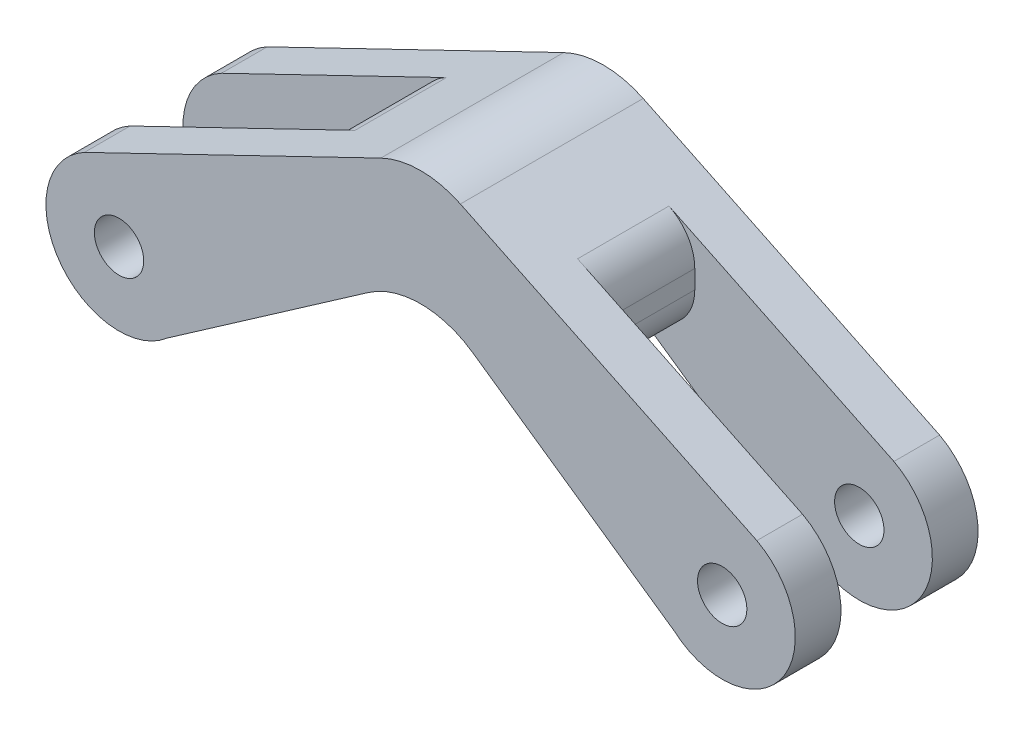
SolidWorks part; units mm, degrees
material "Custom Plastic"
ref_plane "Front Plane" through (0, 0, 0) normal (0, 0, 1) x (1, 0, 0)
ref_plane "Top Plane" through (0, 0, 0) normal (0, 1, 0) x (1, 0, 0)
ref_plane "Right Plane" through (0, 0, 0) normal (1, 0, 0) x (0, 0, -1)
sketch "Sketch3" plane through (0, 0, 0) normal (0, 0, 1) x (1, 0, 0)
  line L0 (18.1918, 14.4291) -> (-2.4073, 4.4734)
  line L1 (17.3271, 5.9068) -> (3.3277, -3.8383)
  line L2 (0, 0) -> (8.5457, 0) construction
  line L5 (6.35, 0) -> (20.955, 8.4322)
  line L7 (20.955, 15.7645) -> (20.955, 8.4322) construction
  line L8 (24.5829, 5.9068) -> (38.5823, -3.8383)
  line L9 (23.7182, 14.4291) -> (44.3173, 4.4734)
  circle A0 centre (0, 0) radius 1.7145
  arc A1 (18.1918, 14.4291) -> (23.7182, 14.4291) centre (20.955, 8.7118) cw
  arc A2 (17.3271, 5.9068) -> (24.5829, 5.9068) centre (20.955, 0.6952) cw
  arc A3 (-2.0096, 4.6656) -> (3.3277, -3.8383) centre (0, 0) ccw
  arc A4 (43.9196, 4.6656) -> (38.5823, -3.8383) centre (41.91, 0) cw
  circle A8 centre (41.91, 0) radius 1.7145
  dimension "D1" = 3.429
  dimension "D2" = 6.35
  dimension "D3" = 41.91
extrude "Boss-Extrude1" add sketch "Sketch3" along normal blind 3.175
ref_plane "Plane1" through (0, 15.24, 0) normal (0, 1, 0) x (1, 0, 0)
sketch "Sketch4" plane through (0, 15.24, 0) normal (0, 1, 0) x (1, 0, 0)
  line L0 (20.955, 6.35) -> (20.955, 0) construction
  line L1 (11.43, 0) -> (30.48, 0)
  line L2 (11.43, 0) -> (11.43, 6.35)
  line L3 (11.43, 6.35) -> (30.48, 6.35)
  line L4 (30.48, 0) -> (30.48, 6.35)
  line L5 (18.1918, 0) -> (23.7182, 0) construction
  dimension "D1" = 19.05
  dimension "D2" = 6.35
extrude "Boss-Extrude2" add sketch "Sketch4" against normal blind 36.83
pattern_linear "LPattern2" count 2 spacing 9.525 along (0, 0, -1) of "Boss-Extrude1"
sketch "Sketch5" plane through (0, 0, 3.175) normal (0, 0, 1) x (1, 0, 0)
  line L0 (36.195, 8.399) -> (23.7182, 14.4291)
  line L1 (30.48, 1.8018) -> (24.5829, 5.9068)
  line L3 (11.43, -23.1173) -> (30.48, -23.1173)
  line L4 (30.48, -23.1173) -> (30.48, 1.8018)
  line L5 (36.195, 8.399) -> (36.195, 15.24)
  line L6 (36.195, 15.24) -> (5.715, 15.24)
  line L8 (20.955, 15.0618) -> (20.955, 7.0452) construction
  line L9 (5.715, 8.399) -> (5.715, 15.24)
  line L10 (11.43, -23.1173) -> (11.43, 1.8018)
  line L11 (11.43, 1.8018) -> (17.3271, 5.9068)
  line L12 (5.715, 8.399) -> (18.1918, 14.4291)
  arc A0 (23.7182, 14.4291) -> (18.1918, 14.4291) centre (20.955, 8.7118) ccw
  arc A1 (24.5829, 5.9068) -> (17.3271, 5.9068) centre (20.955, 0.6952) ccw
extrude "Cut-Extrude1" cut sketch "Sketch5" against normal through all
fillet "Fillet1" radius 3.175 4 edges at (11.43, 11.1611, -3.175) (30.48, 11.1611, -3.175) (30.48, 1.8018, -3.175) (11.43, 1.8018, -3.175)
